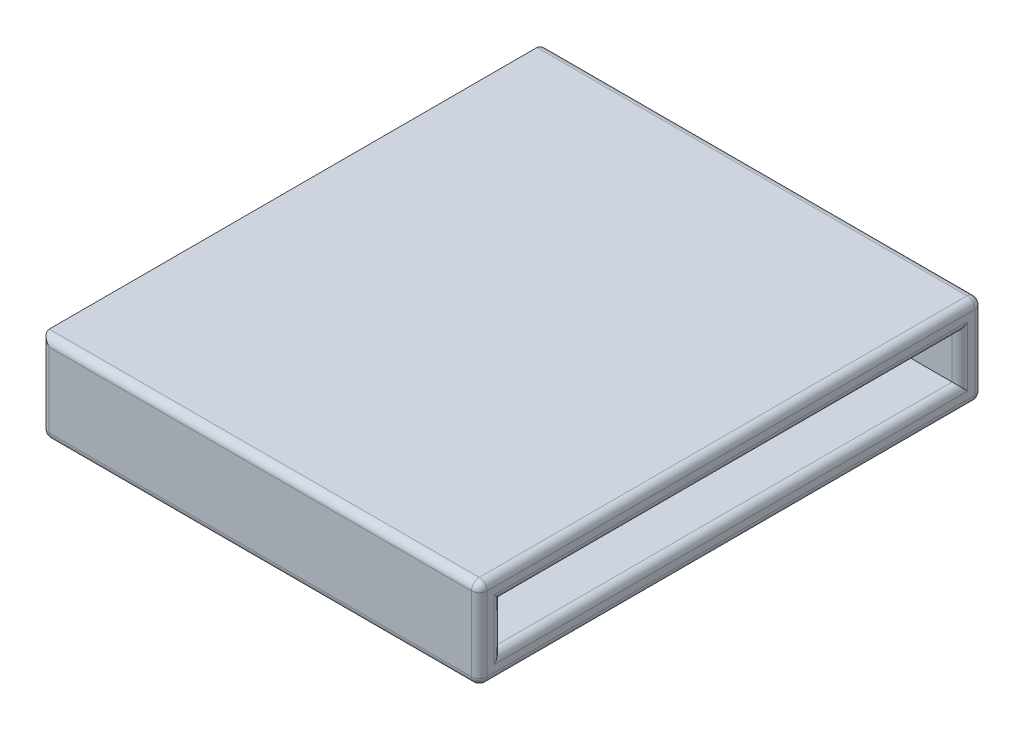
SolidWorks part; units mm, degrees
ref_plane "Front Plane" through (0, 0, 0) normal (0, 0, 1) x (1, 0, 0)
ref_plane "Top Plane" through (0, 0, 0) normal (0, 1, 0) x (1, 0, 0)
ref_plane "Right Plane" through (0, 0, 0) normal (1, 0, 0) x (0, 0, -1)
sketch "Sketch1" plane through (0, 0, 0) normal (0, 1, 0) x (1, 0, 0)
  line L0 (-28, -32.185) -> (-28, 32.185)
  line L1 (-25, -29.185) -> (25, -29.185)
  line L2 (-25, -29.185) -> (-25, 29.185)
  line L3 (-25, 29.185) -> (25, 29.185)
  line L4 (25, -29.185) -> (25, 29.185)
  line L5 (-25, -29.185) -> (25, 29.185) construction
  line L6 (-25, 29.185) -> (25, -29.185) construction
  line L7 (-28, 32.185) -> (28, 32.185)
  line L8 (28, -32.185) -> (28, 32.185)
  line L9 (-28, -32.185) -> (28, -32.185)
  point P0 (0, 0)
  dimension "D1" = 58.37
  dimension "D2" = 50
  dimension "D3" = 3
extrude "Boss-Extrude1" add sketch "Sketch1" along normal blind 11.5 contours L1 L4 L3 L2 | L0 L9 L8 L7 L4 L1 L2 L3
sketch "Sketch2" plane through (-28, 0, 0) normal (-1, 0, 0) x (0, 0, 1)
  line L1 (-32.185, 0) -> (32.185, 0)
  line L2 (-32.185, 0) -> (-32.185, 11.5)
  line L3 (-32.185, 11.5) -> (32.185, 11.5)
  line L4 (32.185, 0) -> (32.185, 11.5)
  line L5 (-32.185, 0) -> (32.185, 11.5) construction
  line L6 (-32.185, 11.5) -> (32.185, 0) construction
  line L7 (-29.285, 2.9) -> (29.285, 2.9)
  line L8 (-29.285, 2.9) -> (-29.285, 8.6)
  line L9 (-29.285, 8.6) -> (29.285, 8.6)
  line L10 (29.285, 2.9) -> (29.285, 8.6)
  line L11 (-29.285, 2.9) -> (29.285, 8.6) construction
  line L12 (-29.285, 8.6) -> (29.285, 2.9) construction
  point P0 (0, 5.75)
  point P6 (0, 5.75)
  dimension "D1" = 5.7
  dimension "D2" = 58.57
extrude "Cut-Extrude1" cut sketch "Sketch2" against normal blind 103 contours L7 L10 L9 L8
fillet "Fillet1" radius 1 19 edges at (0, 11.5, 32.185) (28, 5.75, 32.185) (0, 0, 32.185) (28, 0, 0) (28, 5.75, -32.185) (0, 11.5, -32.185) (0, 0, -32.185) (-28, 5.75, 29.285) (-28, 8.6, 0) (-28, 5.75, -29.285) (-28, 2.9, 0) (-28, 5.75, -32.185) (-28, 5.75, 32.185) (-28, 0, 0) (28, 11.5, 0) (28, 8.6, 0) (28, 5.75, 29.285) (28, 2.9, 0) (28, 5.75, -29.285)
